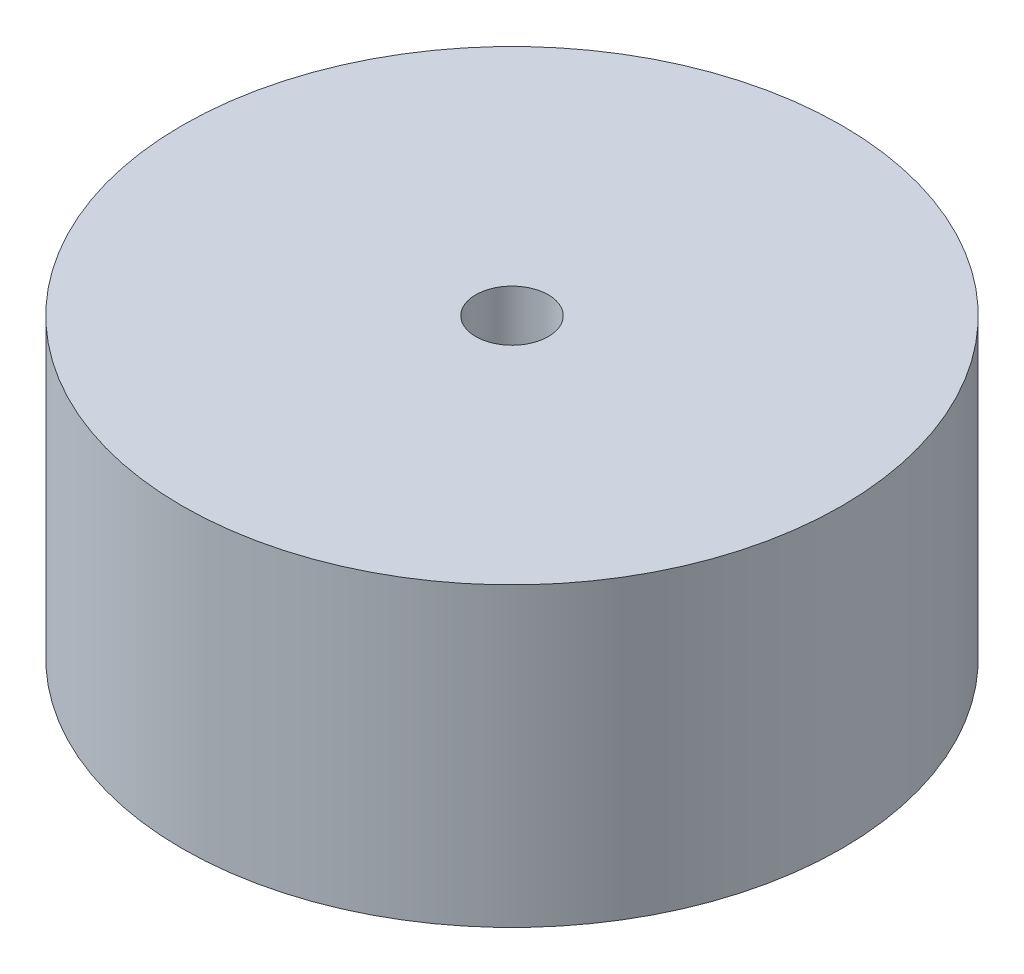
SolidWorks part; units mm, degrees
material "Liga 1060"
ref_plane "Plano frontal" through (0, 0, 0) normal (0, 0, 1) x (1, 0, 0)
ref_plane "Plano superior" through (0, 0, 0) normal (0, 1, 0) x (1, 0, 0)
ref_plane "Plano direito" through (0, 0, 0) normal (1, 0, 0) x (0, 0, -1)
sketch "Esboço1" plane through (0, 0, 0) normal (0, 1, 0) x (1, 0, 0)
  circle A0 centre (0, 0) radius 50
  circle A1 centre (0, 0) radius 5.5
  dimension "D1" = 100
  dimension "D2" = 11
extrude "Ressalto-extrusão1" add sketch "Esboço1" along normal blind 45
